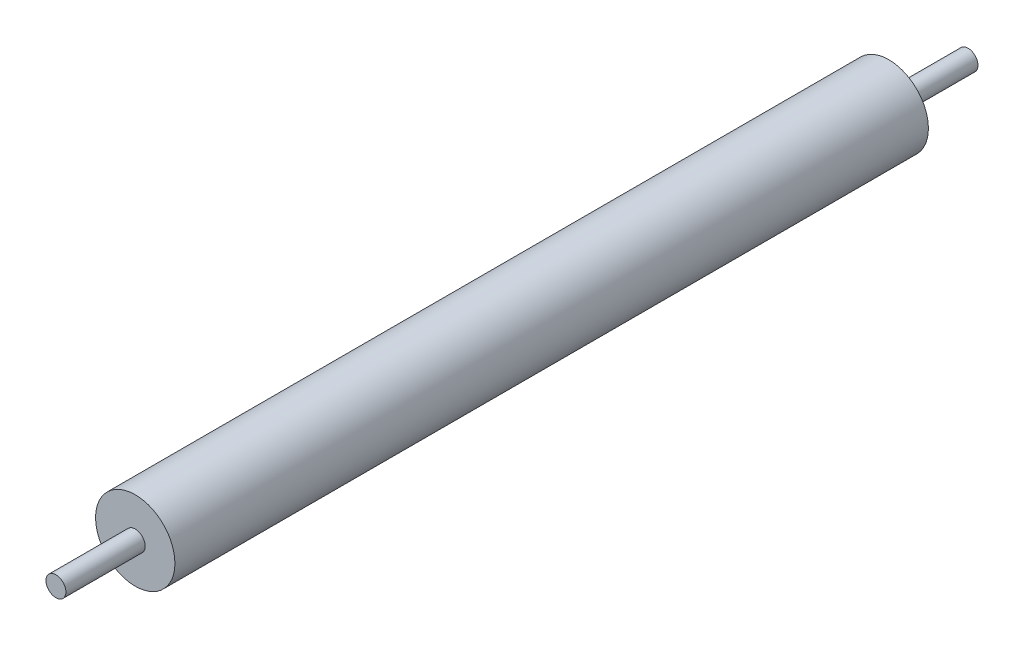
SolidWorks part; units mm, degrees
material "Polyurethane Foam Flexible"
ref_plane "Front Plane" through (0, 0, 0) normal (0, 0, 1) x (1, 0, 0)
ref_plane "Top Plane" through (0, 0, 0) normal (0, 1, 0) x (1, 0, 0)
ref_plane "Right Plane" through (0, 0, 0) normal (1, 0, 0) x (0, 0, -1)
sketch "Sketch1" plane through (0, 0, 0) normal (0, 0, 1) x (1, 0, 0)
  circle A0 centre (0, 0) radius 25.4
extrude "Boss-Extrude1" add sketch "Sketch1" along normal blind 584.2 contours A0
sketch "Sketch2" plane through (0, 0, 0) normal (0, 0, 1) x (1, 0, 0)
  circle A0 centre (0, 0) radius 6.3619
extrude "Cut-Extrude1" cut sketch "Sketch2" along normal blind 50.8 flip side to cut contours A0
sketch "Sketch5" plane through (0, 0, 584.2) normal (0, 0, 1) x (1, 0, 0)
  circle A0 centre (0, 0) radius 6.3779
extrude "Cut-Extrude4" cut sketch "Sketch5" against normal blind 50.8 flip side to cut
